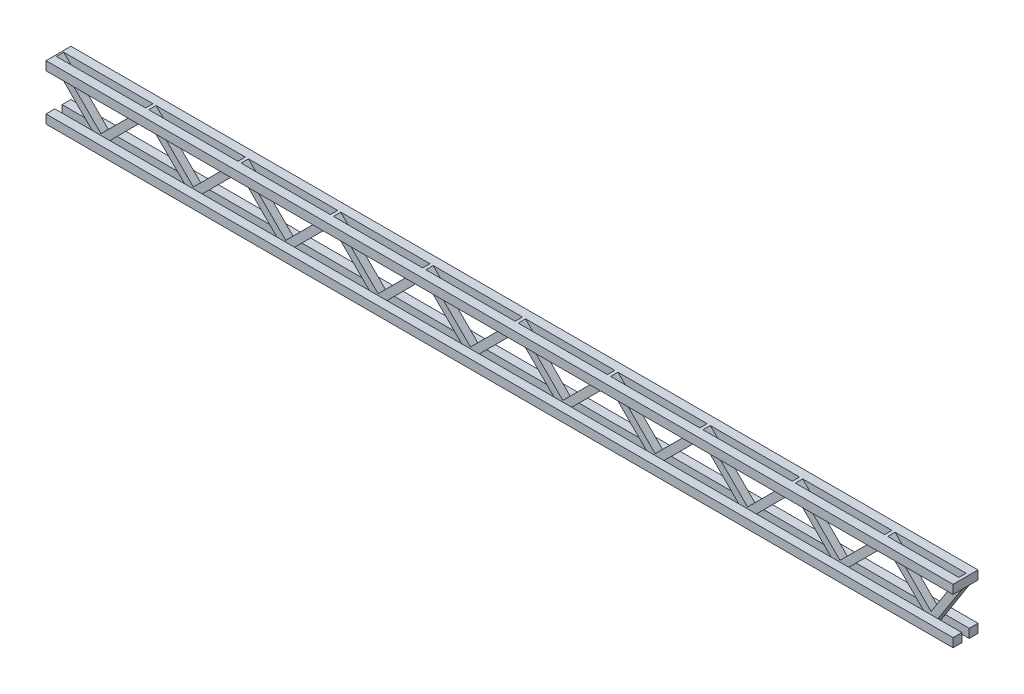
SolidWorks part; units mm, degrees
ref_plane "Alzado" through (0, 0, 0) normal (0, 0, 1) x (1, 0, 0)
ref_plane "Planta" through (0, 0, 0) normal (0, 1, 0) x (1, 0, 0)
ref_plane "Vista lateral" through (0, 0, 0) normal (1, 0, 0) x (0, 0, -1)
sketch "Croquis1" plane through (0, 0, 0) normal (0, 0, 1) x (1, 0, 0)
  line L0 (0, 0) -> (0, 800) construction
  line L1 (-7855.6, -76.2) -> (7855.6, -76.2)
  line L2 (-7855.6, -76.2) -> (-7855.6, 76.2)
  line L3 (-7855.6, 76.2) -> (7855.6, 76.2)
  line L4 (7855.6, -76.2) -> (7855.6, 76.2)
  line L5 (-7855.6, -76.2) -> (7855.6, 76.2) construction
  line L6 (-7855.6, 76.2) -> (7855.6, -76.2) construction
  line L7 (-7855.6, 76.2) -> (-7855.6, 723.8) construction
  line L8 (-7855.6, 723.8) -> (7855.6, 723.8)
  line L9 (-7855.6, 723.8) -> (-7855.6, 876.2)
  line L10 (-7855.6, 876.2) -> (7855.6, 876.2)
  line L11 (7855.6, 723.8) -> (7855.6, 876.2)
  line L12 (-7855.6, 723.8) -> (7855.6, 876.2) construction
  line L13 (-7855.6, 876.2) -> (7855.6, 723.8) construction
  point P0 (0, 0)
  dimension "D1" = 152.4
  dimension "D2" = 15711.2
  dimension "D3" = 800
  dimension "D4" = 152.4
extrude "Saliente-Extruir1" add sketch "Croquis1" along normal blind 152.4
sketch "Croquis5" plane through (0, 0, 152.4) normal (0, 0, 1) x (1, 0, 0)
  line L0 (-7855.6, 723.8) -> (-7055.6, -76.2)
  line L2 (-7855.6, -76.2) -> (7855.6, -76.2) construction
  line L4 (-7055.6, -76.2) -> (-6255.6, 723.8)
  line L5 (-7855.6, 723.8) -> (7855.6, 723.8) construction
  line L6 (-6255.6, 723.8) -> (-5455.6, -76.2)
  line L7 (-5455.6, -76.2) -> (-4655.6, 723.8)
  line L8 (-4655.6, 723.8) -> (-3855.6, -76.2)
  line L9 (-3855.6, -76.2) -> (-3055.6, 723.8)
  line L10 (-3055.6, 723.8) -> (-2255.6, -76.2)
  line L11 (-2255.6, -76.2) -> (-1455.6, 723.8)
  line L12 (-1455.6, 723.8) -> (-655.6, -76.2)
  line L13 (-655.6, -76.2) -> (144.4, 723.8)
  line L14 (144.4, 723.8) -> (944.4, -76.2)
  line L15 (944.4, -76.2) -> (1744.4, 723.8)
  line L16 (1744.4, 723.8) -> (2544.4, -76.2)
  line L17 (2544.4, -76.2) -> (3344.4, 723.8)
  line L18 (3344.4, 723.8) -> (4144.4, -76.2)
  line L19 (4144.4, -76.2) -> (4944.4, 723.8)
  line L20 (4944.4, 723.8) -> (5744.4, -76.2)
  line L21 (5744.4, -76.2) -> (6544.4, 723.8)
  line L22 (6544.4, 723.8) -> (7344.4, -76.2)
  line L23 (7344.4, -76.2) -> (7855.6, 723.8)
  line L24 (-7765.7974, 813.6026) -> (-7055.6, 103.4051)
  line L25 (-7055.6, 103.4051) -> (-6282.8051, 876.2)
  line L26 (-6228.3949, 876.2) -> (-5455.6, 103.4051)
  line L27 (-5455.6, 103.4051) -> (-4682.8051, 876.2)
  line L28 (-4628.3949, 876.2) -> (-3855.6, 103.4051)
  line L29 (-3855.6, 103.4051) -> (-3082.8051, 876.2)
  line L30 (-3028.3949, 876.2) -> (-2255.6, 103.4051)
  line L31 (-2255.6, 103.4051) -> (-1482.8051, 876.2)
  line L32 (-1428.3949, 876.2) -> (-655.6, 103.4051)
  line L33 (-655.6, 103.4051) -> (117.1949, 876.2)
  line L34 (171.6051, 876.2) -> (944.4, 103.4051)
  line L35 (944.4, 103.4051) -> (1717.1949, 876.2)
  line L36 (1771.6051, 876.2) -> (2544.4, 103.4051)
  line L37 (2544.4, 103.4051) -> (3317.1949, 876.2)
  line L38 (3371.6051, 876.2) -> (4144.4, 103.4051)
  line L39 (4144.4, 103.4051) -> (4917.1949, 876.2)
  line L40 (4971.6051, 876.2) -> (5744.4, 103.4051)
  line L41 (5744.4, 103.4051) -> (6517.1949, 876.2)
  line L42 (6571.6051, 876.2) -> (7322.4679, 125.3372)
  line L43 (7322.4679, 125.3372) -> (7748.583, 792.1839)
  line L44 (-7765.7974, 813.6026) -> (-7828.3949, 876.2)
  line L45 (7855.6, 876.2) -> (-7855.6, 876.2) construction
  line L46 (-7828.3949, 876.2) -> (-7855.6, 876.2)
  line L47 (-7855.6, 876.2) -> (-7855.6, 723.8)
  line L48 (-7855.6, 723.8) -> (-7855.8476, 724.568)
  line L49 (-6282.8051, 876.2) -> (-6228.3949, 876.2)
  line L50 (-7055.6, 103.4051) -> (-6255.6, 903.4051) construction
  line L51 (-6255.6, 903.4051) -> (-5455.6, 103.4051) construction
  line L52 (-4682.8051, 876.2) -> (-4628.3949, 876.2)
  line L53 (-5455.6, 103.4051) -> (-4655.6, 903.4051) construction
  line L54 (-4655.6, 903.4051) -> (-3855.6, 103.4051) construction
  line L55 (-3082.8051, 876.2) -> (-3028.3949, 876.2)
  line L56 (-3855.6, 103.4051) -> (-3055.6, 903.4051) construction
  line L57 (-3055.6, 903.4051) -> (-2255.6, 103.4051) construction
  line L58 (-1482.8051, 876.2) -> (-1428.3949, 876.2)
  line L59 (-2255.6, 103.4051) -> (-1455.6, 903.4051) construction
  line L60 (-1455.6, 903.4051) -> (-655.6, 103.4051) construction
  line L61 (117.1949, 876.2) -> (171.6051, 876.2)
  line L62 (-655.6, 103.4051) -> (144.4, 903.4051) construction
  line L63 (144.4, 903.4051) -> (944.4, 103.4051) construction
  line L64 (1717.1949, 876.2) -> (1771.6051, 876.2)
  line L65 (944.4, 103.4051) -> (1744.4, 903.4051) construction
  line L66 (1744.4, 903.4051) -> (2544.4, 103.4051) construction
  line L67 (3317.1949, 876.2) -> (3371.6051, 876.2)
  line L68 (2544.4, 103.4051) -> (3344.4, 903.4051) construction
  line L69 (3344.4, 903.4051) -> (4144.4, 103.4051) construction
  line L70 (4917.1949, 876.2) -> (4971.6051, 876.2)
  line L71 (4144.4, 103.4051) -> (4944.4, 903.4051) construction
  line L72 (4944.4, 903.4051) -> (5744.4, 103.4051) construction
  line L73 (6517.1949, 876.2) -> (6571.6051, 876.2)
  line L74 (5744.4, 103.4051) -> (6544.4, 903.4051) construction
  line L75 (6544.4, 903.4051) -> (7322.4679, 125.3372) construction
  line L76 (7748.583, 792.1839) -> (7802.2693, 876.2)
  line L77 (7802.2693, 876.2) -> (7855.6, 876.2)
  line L78 (7855.6, 876.2) -> (7855.6, 723.8)
  line M1 (7855.6, 723.8) -> (7855.6, 876.2)
  line M2 (7855.6, 876.2) -> (-7855.6, 876.2)
  line M3 (-7855.6, 876.2) -> (-7855.6, 723.8)
  line M4 (-7855.6, 723.8) -> (7855.6, 723.8)
  dimension "D1" = 127
extrude "Saliente-Extruir4" add sketch "Croquis5" along normal blind 127 contours L76 L43 M4 M1 M2 | L43 L42 L22 L23 M4 | L42 L41 M2 M4 | L41 L40 L20 L21 M4 | L40 L39 M2 M4 | L39 L38 L18 L19 M4 | L38 L37 M2 M4 | L37 L36 L16 L17 M4 | L36 L35 M2 M4 | L35 L34 L14 L15 M4 | L34 L33 M2 M4 | L33 L32 L12 L13 M4 | L32 L31 M2 M4 | L31 L30 L10 L11 M4 | L30 L29 M2 M4 | L29 L28 L8 L9 M4 | L28 L27 M2 M4 | L27 L26 L6 L7 M4 | L26 L25 M2 M4 | L25 L24 L0 L4 M4 | L24 L44 M2 M3 M4
sketch "Croquis6" plane through (0, 0, 279.4) normal (0, 0, 1) x (1, 0, 0)
  line L0 (-7855.6, 876.2) -> (-7855.6, 723.8)
  line L1 (-7855.6, 723.8) -> (7855.6, 723.8)
  line L2 (7855.6, 723.8) -> (7855.6, 876.2)
  line L3 (7855.6, 876.2) -> (-7855.6, 876.2)
  line L4 (-7855.6, 76.2) -> (7855.6, 76.2)
  line L5 (7855.6, 76.2) -> (7855.6, -76.2)
  line L6 (7855.6, -76.2) -> (-7855.6, -76.2)
  line L7 (-7855.6, -76.2) -> (-7855.6, 76.2)
extrude "Saliente-Extruir5" add sketch "Croquis6" along normal blind 152.4
